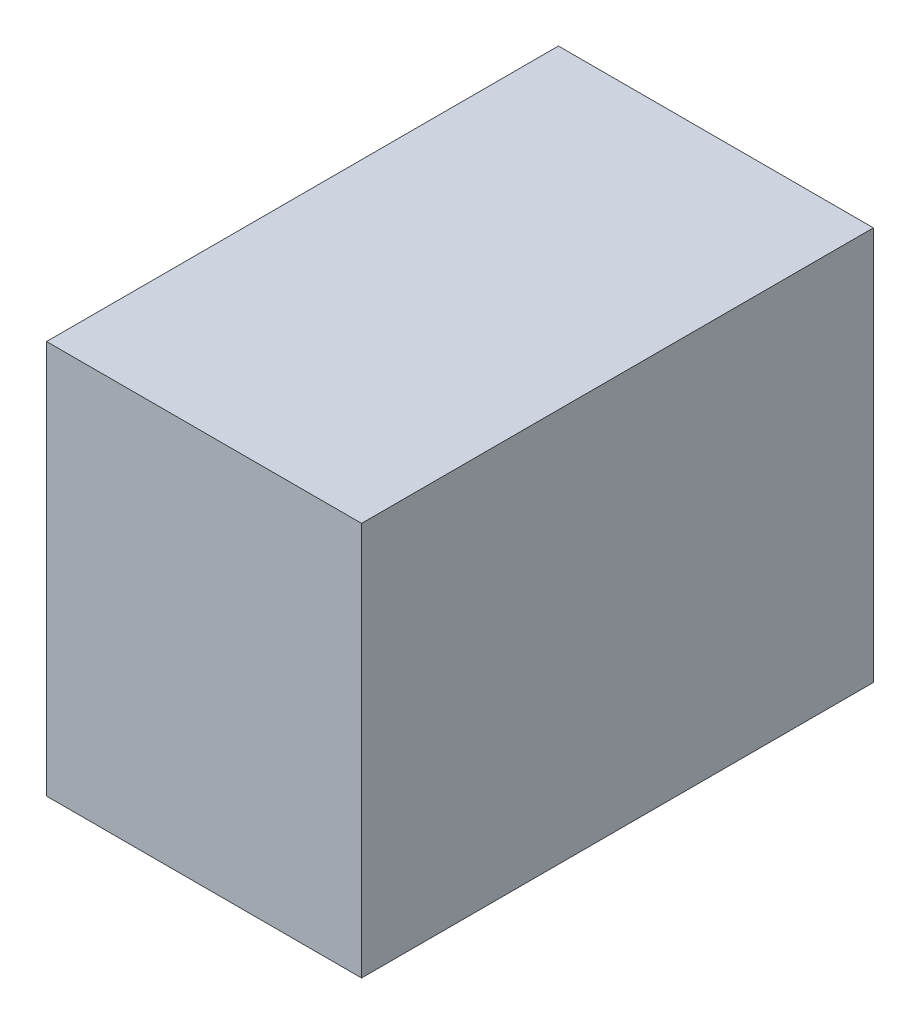
SolidWorks part; units mm, degrees
material "Nylon 6/10"
ref_plane "Front Plane" through (0, 0, 0) normal (0, 0, 1) x (1, 0, 0)
ref_plane "Top Plane" through (0, 0, 0) normal (0, 1, 0) x (1, 0, 0)
ref_plane "Right Plane" through (0, 0, 0) normal (1, 0, 0) x (0, 0, -1)
sketch "Esboço1" plane through (0, 0, 0) normal (0, 0, 1) x (1, 0, 0)
  line L0 (0, 0) -> (80, 0)
  line L1 (80, 0) -> (80, 100)
  line L2 (80, 100) -> (0, 100)
  line L3 (0, 100) -> (0, 0)
  dimension "D1" = 80
  dimension "D2" = 100
extrude "Ressalto-extrusão1" add sketch "Esboço1" along normal blind 130
